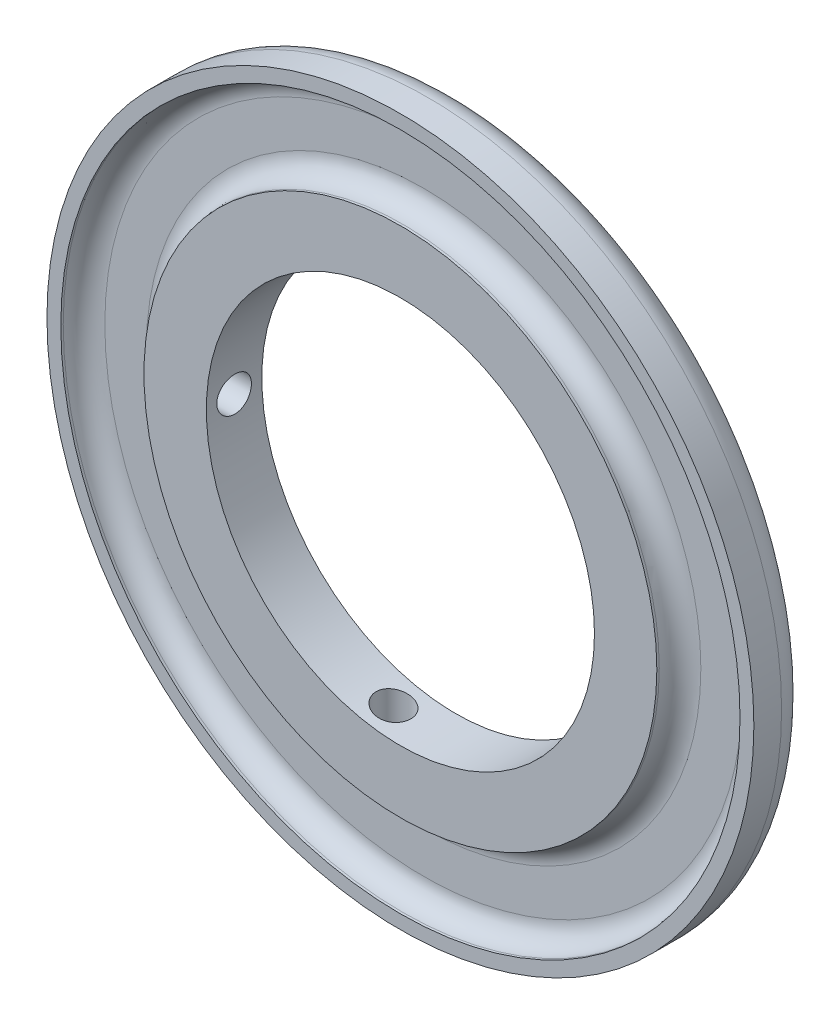
SolidWorks part; units mm, degrees
ref_plane "Front Plane" through (0, 0, 0) normal (0, 0, 1) x (1, 0, 0)
ref_plane "Top Plane" through (0, 0, 0) normal (0, 1, 0) x (1, 0, 0)
ref_plane "Right Plane" through (0, 0, 0) normal (1, 0, 0) x (0, 0, -1)
sketch "Sketch1" plane through (0, 0, 0) normal (0, 0, 1) x (1, 0, 0)
  circle A0 centre (0, 0) radius 25.5
  dimension "D1" = 51
extrude "Boss-Extrude1" add sketch "Sketch1" along normal blind 4
sketch "Sketch2" plane through (0, 0, 4) normal (0, 0, 1) x (1, 0, 0)
  circle A0 centre (0, 0) radius 24.5
  circle A1 centre (0, 0) radius 18.5
  dimension "D1" = 49
  dimension "D2" = 37
extrude "Cut-Extrude1" cut sketch "Sketch2" against normal blind 1.675
fillet "Fillet1" radius 1.5 2 edges at (18.5, 0, 2.325) (24.5, 0, 2.325)
sketch "Sketch3" plane through (0, 0, 4) normal (0, 0, 1) x (1, 0, 0)
  circle A0 centre (0, 0) radius 14
  dimension "D1" = 28
extrude "Cut-Extrude2" cut sketch "Sketch3" against normal blind 4
fillet "Fillet2" radius 2 1 edges at (25.5, 0, 0)
sketch "Sketch4" plane through (0, 0, 0) normal (1, 0, 0) x (0, 0, -1)
  line L0 (-23.0581, 0) -> (26.1123, 0) construction
  circle A0 centre (-2, 0) radius 1.25
  dimension "D1" = 2.5
  dimension "D2" = 2
extrude "Cut-Extrude3" cut sketch "Sketch4" against normal blind 17
sketch "Sketch5" plane through (0, 0, 0) normal (0, 1, 0) x (1, 0, 0)
  line L0 (0, 23.8034) -> (0, -29.2913) construction
  circle A0 centre (-2.5, -2) radius 1.25
  dimension "D1" = 2.5
  dimension "D2" = 2
  dimension "D3" = 2.5
extrude "Cut-Extrude5" cut sketch "Sketch5" against normal mid plane 34
